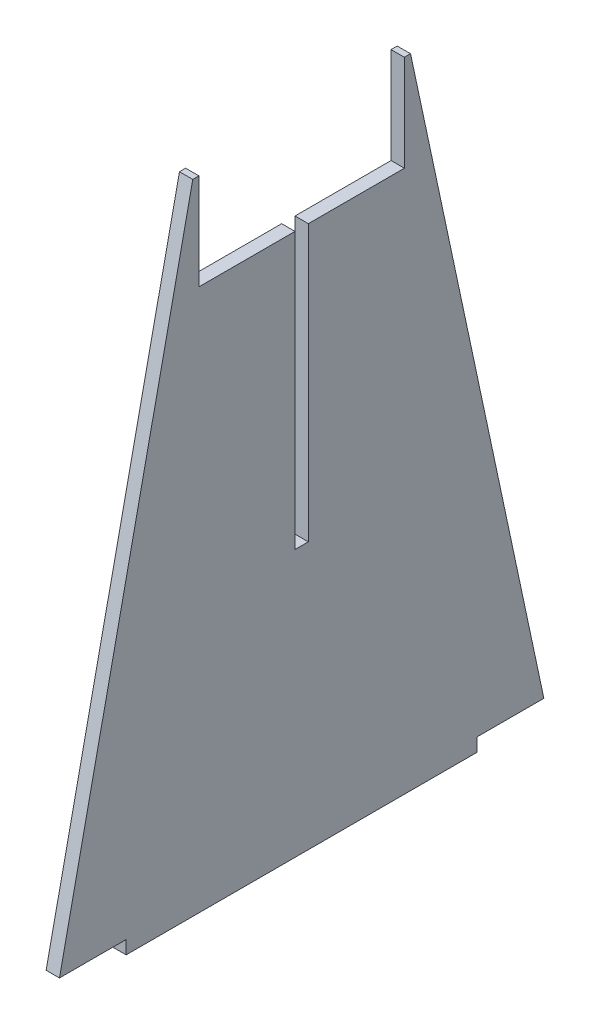
SolidWorks part; units mm, degrees
ref_plane "Спереди" through (0, 0, 0) normal (0, 0, 1) x (1, 0, 0)
ref_plane "Сверху" through (0, 0, 0) normal (0, 1, 0) x (1, 0, 0)
ref_plane "Справа" through (0, 0, 0) normal (1, 0, 0) x (0, 0, -1)
sketch "Эскиз1" plane through (0, 0, 0) normal (1, 0, 0) x (0, 0, -1)
  line L3 (29.1133, 119) -> (54.5, 0)
  line L4 (54.5, 0) -> (39.5, 0)
  line L5 (39.5, 0) -> (39.5, -3)
  line L6 (39.5, -3) -> (-39.5, -3)
  line L9 (1.5, 57) -> (1.5, 119)
  line L10 (0, -3) -> (0, 75) construction
  line L11 (-1.5, 57) -> (-1.5, 119)
  line L12 (-39.5, 0) -> (-39.5, -3)
  line L13 (-54.5, 0) -> (-39.5, 0)
  line L14 (-29.1133, 119) -> (-54.5, 0)
  line L16 (-1.5, 119) -> (-29.1133, 119)
  line L17 (29.1133, 119) -> (1.5, 119)
  line L20 (1.5, 57) -> (-1.5, 57)
extrude "Бобышка-Вытянуть1" add sketch "Эскиз1" along normal blind 3
sketch "Sketch1" plane through (3, 0, 0) normal (1, 0, 0) x (0, 0, -1)
  line L0 (-29.1133, 119) -> (-24.5, 140.625)
  line L1 (-24.5, 140.625) -> (-23.1133, 140.625)
  line L2 (-23.1133, 140.625) -> (-23.1133, 119)
  line L3 (-1.5, 119) -> (-29.1133, 119) construction
  line L4 (29.1133, 119) -> (24.5, 140.625)
  line L5 (24.5, 140.625) -> (23.1133, 140.625)
  line L6 (23.1133, 140.625) -> (23.1133, 119)
  line L7 (29.1133, 119) -> (1.5, 119) construction
  line L8 (-29.1133, 119) -> (-54.5, 0) construction
  line L9 (54.5, 0) -> (29.1133, 119) construction
  line L10 (-23.1133, 119) -> (-29.1133, 119)
  line L11 (29.1133, 119) -> (23.1133, 119)
  dimension "D1" = 6
  dimension "D2" = 6
  dimension "D3" = 49
extrude "Boss-Extrude1" add sketch "Sketch1" against normal up to surface (3 mm away) contours L2 L10 L0 L1 | L6 L11 L4 L5 up to face at (0, 48.6667, 0)
